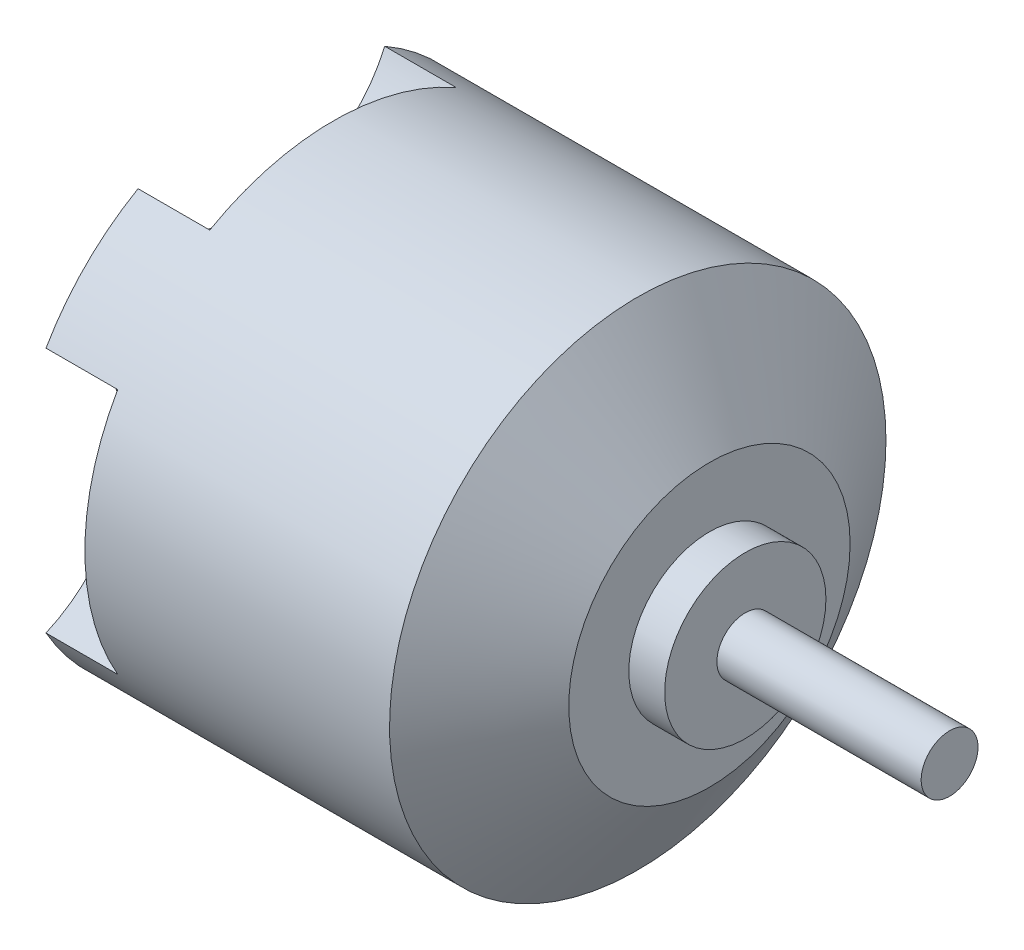
SolidWorks part; units mm, degrees
ref_plane "Front Plane" through (0, 0, 0) normal (0, 0, 1) x (1, 0, 0)
ref_plane "Top Plane" through (0, 0, 0) normal (0, 1, 0) x (1, 0, 0)
ref_plane "Right Plane" through (0, 0, 0) normal (1, 0, 0) x (0, 0, -1)
sketch "Sketch2" plane through (0, 0, 0) normal (1, 0, 0) x (0, 0, -1)
  circle A0 centre (0, 0) radius 13.85
  dimension "D1" = 27.7
extrude "Boss-Extrude1" add sketch "Sketch2" along normal blind 25
sketch "Sketch3" plane through (25, 0, 0) normal (1, 0, 0) x (0, 0, -1)
  circle A0 centre (0, 0) radius 4.5
  dimension "D1" = 9
extrude "Boss-Extrude2" add sketch "Sketch3" along normal blind 2
sketch "Sketch4" plane through (0, 0, 0) normal (-1, 0, 0) x (0, 0, 1)
  arc A0 (12.0191, -6.8822) -> (12.0191, 6.8822) centre (15, 0) cw
  circle A1 centre (0, 0) radius 13.85 construction
  arc A2 (12.0191, -6.8822) -> (12.0191, 6.8822) centre (0, 0) ccw
  point P3 (0, 0)
  point P7 (0, 0)
  point P8 (0, 0)
  point P9 (11.9614, -6.982)
  point P10 (0, 0)
  point P11 (11.9915, -6.93)
  point P12 (12.2918, -6.3823)
  point P13 (11.8474, -7.1737)
  point P14 (16.5897, 0)
  point P15 (11.687, -7.4321)
  point P16 (15.6305, 0)
  point P17 (13.85, 0)
  point P18 (11.4941, -7.7271)
  point P19 (0, 0)
  point P20 (14.9149, 0)
  dimension "D1" = 7.5
  dimension "D2" = 15
extrude "Cut-Extrude1" cut sketch "Sketch4" against normal blind 4
pattern_circular "CirPattern1" count 4 over 360 about axis through (0, 0, 0) along (1, 0, 0) of "Cut-Extrude1"
hole_wizard "Ø3.0 (3) Diameter Hole1" positions "Sketch8" profile "Sketch9" hole size "Ø3.0" standard "ANSI Metric"
sketch "Sketch8" plane through (0, 0, 0) normal (-1, 0, 0) x (0, 0, 1)
  line L1 (-5.5114, -5.7987) -> (5.5114, -5.7987) construction
  line L2 (-5.5114, -5.7987) -> (-5.5114, 5.7987) construction
  line L3 (-5.5114, 5.7987) -> (5.5114, 5.7987) construction
  line L4 (5.5114, -5.7987) -> (5.5114, 5.7987) construction
  line L5 (-5.5114, -5.7987) -> (5.5114, 5.7987) construction
  line L6 (-5.5114, 5.7987) -> (5.5114, -5.7987) construction
  circle A0 centre (0, 0) radius 8 construction
  point P6 (5.5114, 5.7987)
  point P129 (-5.5114, -5.7987)
  point P130 (-5.5114, 5.7987)
  point P131 (5.5114, -5.7987)
  dimension "D1" = 16
sketch "Sketch9" plane through (0, -5.7987, 5.5114) normal (0, 1, 0) x (0, 0, 1)
  line L0 (0, 0) -> (0, 4.9003)
  line L1 (0, 4.9003) -> (1.5, 3.999)
  line L2 (1.5, 3.999) -> (1.5, 0)
  line L5 (1.5, 0) -> (0, 0)
  line L10 (0, 4.9003) -> (-1.5, 3.999) construction
  line L11 (0, -6.35) -> (0, 107.95) construction
  dimension "Hole Dia." = 3
  dimension "Hole Depth" = 3.999
  dimension "Drill Angle" = 118
sketch "Sketch10" plane through (25, 0, 0) normal (1, 0, 0) x (0, 0, -1)
  circle A0 centre (0, 0) radius 1.585
  dimension "D1" = 3.17
extrude "Boss-Extrude3" add sketch "Sketch10" along direction (1, 0, 0) on the side against the normal blind 40 from offset 13.4
chamfer "Chamfer2" distance 4 distance2 6 1 edges at (25, 0, -13.85)
